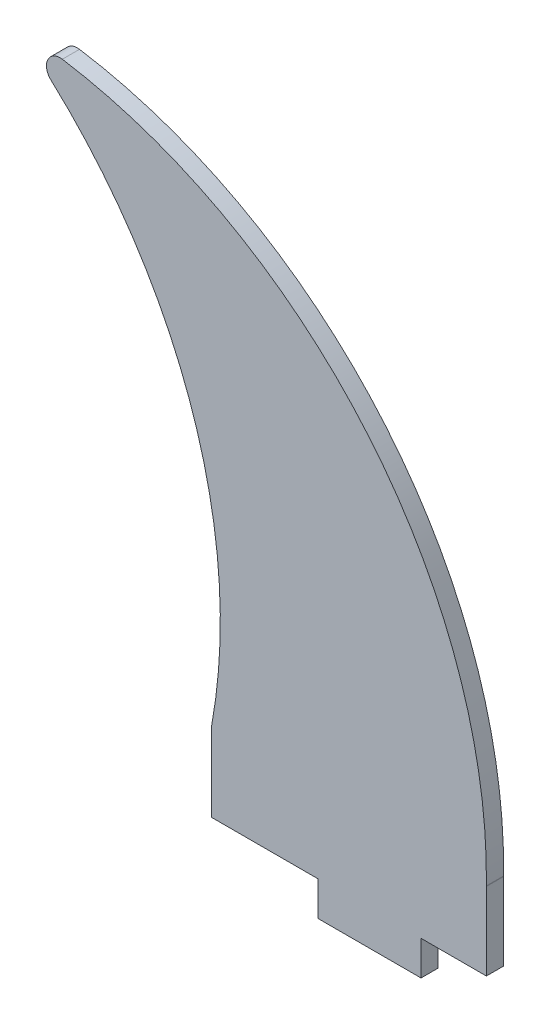
SolidWorks part; units mm, degrees
ref_plane "Front Plane" through (0, 0, 0) normal (0, 0, 1) x (1, 0, 0)
ref_plane "Top Plane" through (0, 0, 0) normal (0, 1, 0) x (1, 0, 0)
ref_plane "Right Plane" through (0, 0, 0) normal (1, 0, 0) x (0, 0, -1)
sketch "Sketch1" plane through (0, 0, 0) normal (0, 0, 1) x (1, 0, 0)
  line L5 (19.7016, 0) -> (38.7516, 0)
  line L6 (19.7016, 0) -> (19.7016, -6.35)
  line L7 (19.7016, -6.35) -> (38.7516, -6.35)
  line L8 (38.7516, 0) -> (38.7516, -6.35)
  line L9 (0, 0) -> (50.8228, 0)
  line L10 (0, 0) -> (0, 14.3805)
  line L11 (0, 14.3805) -> (50.8228, 14.3805)
  line L12 (50.8228, 0) -> (50.8228, 14.3805)
  arc A2 (0, 14.3805) -> (-36.0162, 108.4835) centre (-94.4552, 32.1733) ccw
  arc A3 (-36.0162, 108.4835) -> (50.8228, 14.3805) centre (-42.1159, 15.7353) cw
  point P12 (-27.2149, 58.2664)
  point P14 (-11.4036, 55.0068)
  point P15 (-30.6244, 84.163)
  point P16 (-36.0162, 108.4835)
  dimension "D1" = 6.35
  dimension "D3" = 19.7016
  dimension "D2" = 19.05
extrude "Boss-Extrude2" add sketch "Sketch1" along normal blind 3.175 contours A3 A2 L11 | L9 L12 L11 L10 L5 | L8 L5 L6 L7
fillet "Fillet2" radius 6.35 2 edges at (50.8228, 14.3805, 1.5875) (0, 14.3805, 1.5875)
fillet "Fillet3" radius 2.54 1 edges at (-36.0162, 108.4835, 1.5875)
